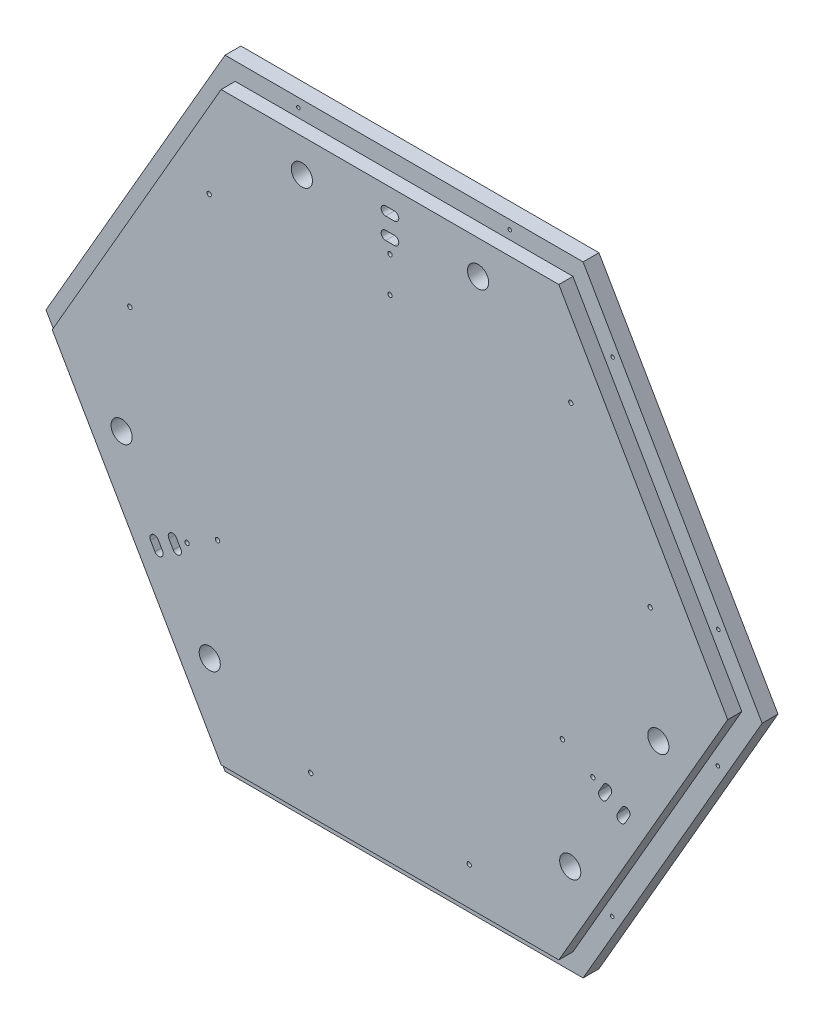
SolidWorks part; units mm, degrees
ref_plane "Front Plane" through (0, 0, 0) normal (0, 0, 1) x (1, 0, 0)
ref_plane "Top Plane" through (0, 0, 0) normal (0, 1, 0) x (1, 0, 0)
ref_plane "Right Plane" through (0, 0, 0) normal (1, 0, 0) x (0, 0, -1)
sketch "Sketch1" plane through (0, 0, 0) normal (0, 0, 1) x (1, 0, 0)
  line L1 (105.6551, 183) -> (-105.6551, 183)
  line L2 (-105.6551, 183) -> (-211.3102, 0)
  line L3 (-211.3102, 0) -> (-105.6551, -183)
  line L4 (-105.6551, -183) -> (105.6551, -183)
  line L5 (105.6551, -183) -> (211.3102, 0)
  line L6 (211.3102, 0) -> (105.6551, 183)
  circle A0 centre (0, 0) radius 183 construction
  circle A1 centre (0, 0) radius 75 construction
  dimension "D1" = 150
  dimension "D2" = 366
extrude "Boss-Extrude1" add sketch "Sketch1" along normal blind 17
sketch "Sketch3" plane through (0, 0, 17) normal (0, 0, 1) x (1, 0, 0)
  line L0 (0, 183) -> (0, 147) construction
  line L1 (211.3102, 0) -> (105.6551, 183) construction
  line L2 (105.6551, 183) -> (-105.6551, 183) construction
  line L3 (-105.6551, 183) -> (-211.3102, 0) construction
  line L4 (-211.3102, 0) -> (-105.6551, -183) construction
  line L5 (-105.6551, -183) -> (105.6551, -183) construction
  line L6 (105.6551, -183) -> (211.3102, 0) construction
  line L7 (158.4826, -91.5) -> (127.3057, -73.5) construction
  line L8 (-158.4826, -91.5) -> (-127.3057, -73.5) construction
  line L9 (-50, 147) -> (0, 147) construction
  line L10 (0, 147) -> (50, 147) construction
  line L11 (-152.3057, -30.1987) -> (-127.3057, -73.5) construction
  line L12 (-127.3057, -73.5) -> (-102.3057, -116.8013) construction
  line L13 (102.3057, -116.8013) -> (127.3057, -73.5) construction
  line L14 (127.3057, -73.5) -> (152.3057, -30.1987) construction
  circle A0 centre (0, 0) radius 183 construction
  circle A1 centre (50, 147) radius 6
  circle A2 centre (-50, 147) radius 6
  circle A3 centre (-152.3057, -30.1987) radius 6
  circle A4 centre (-102.3057, -116.8013) radius 6
  circle A5 centre (102.3057, -116.8013) radius 6
  circle A6 centre (152.3057, -30.1987) radius 6
  dimension "D1" = 366
  dimension "D4" = 12
  dimension "D2" = 36
  dimension "D3" = 50
  dimension "D5" = 147
extrude "Cut-Extrude1" cut sketch "Sketch3" against normal blind 10
sketch "Sketch4" plane through (0, 0, 17) normal (0, 0, 1) x (1, 0, 0)
  line L12 (191.6803, 0) -> (95.8401, 166)
  line L13 (95.8401, 166) -> (-95.8401, 166)
  line L14 (-95.8401, 166) -> (-191.6803, 0)
  line L15 (-191.6803, 0) -> (-95.8401, -166)
  line L16 (-95.8401, -166) -> (95.8401, -166)
  line L17 (95.8401, -166) -> (191.6803, 0)
  line L18 (191.6803, 0) -> (95.8401, 166)
  line L19 (95.8401, 166) -> (-95.8401, 166)
  line L20 (-95.8401, 166) -> (-191.6803, 0)
  line L21 (-191.6803, 0) -> (-95.8401, -166)
  line L22 (-95.8401, -166) -> (95.8401, -166)
  line L23 (95.8401, -166) -> (191.6803, 0)
  dimension "D1" = 17
extrude "Cut-Extrude2" cut sketch "Sketch4" against normal blind 8 flip side to cut
sketch "Sketch5" plane through (0, 0, 17) normal (0, 0, 1) x (1, 0, 0)
  line L0 (50, 147) -> (-50, 147) construction
  line L1 (-152.3057, -30.1987) -> (-102.3057, -116.8013) construction
  line L2 (102.3057, -116.8013) -> (152.3057, -30.1987) construction
  line L3 (97.8609, -56.5) -> (127.3057, -73.5) construction
  line L4 (122.1096, -70.5) -> (132.5019, -76.5) construction
  line L5 (-122.1096, -70.5) -> (-132.5019, -76.5) construction
  line L6 (-97.8609, -56.5) -> (-127.3057, -73.5) construction
  line L7 (-127.3057, -73.5) -> (-115.1814, -66.5) construction
  line L8 (-123.3596, -68.3349) -> (-120.8596, -72.6651) construction
  line L9 (-121.1945, -67.0849) -> (-118.6945, -71.4151)
  line L10 (-125.5246, -69.5849) -> (-123.0246, -73.9151)
  line L11 (-133.7519, -74.3349) -> (-131.2519, -78.6651) construction
  line L12 (-131.5868, -73.0849) -> (-129.0868, -77.4151)
  line L13 (-135.917, -75.5849) -> (-133.417, -79.9151)
  line L14 (127.3057, -73.5) -> (115.1814, -66.5) construction
  line L15 (120.8596, -72.6651) -> (123.3596, -68.3349) construction
  line L16 (118.6945, -71.4151) -> (121.1945, -67.0849)
  line L17 (123.0246, -73.9151) -> (125.5246, -69.5849)
  line L18 (131.2519, -78.6651) -> (133.7519, -74.3349) construction
  line L19 (129.0868, -77.4151) -> (131.5868, -73.0849)
  line L20 (133.417, -79.9151) -> (135.917, -75.5849)
  line L21 (0, 113) -> (0, 147) construction
  line L22 (0, 141) -> (0, 147) construction
  line L23 (0, 147) -> (0, 133) construction
  line L24 (2.5, 141) -> (-2.5, 141) construction
  line L25 (2.5, 138.5) -> (-2.5, 138.5)
  line L26 (2.5, 143.5) -> (-2.5, 143.5)
  line L27 (2.5, 153) -> (-2.5, 153) construction
  line L28 (2.5, 150.5) -> (-2.5, 150.5)
  line L29 (2.5, 155.5) -> (-2.5, 155.5)
  line L30 (105.6551, -183) -> (211.3102, 0) construction
  line L31 (105.6551, 183) -> (-105.6551, 183) construction
  line L32 (0, 147) -> (0, 153) construction
  line L33 (-211.3102, 0) -> (-105.6551, -183) construction
  circle A0 centre (115.1814, -66.5) radius 1.25
  circle A1 centre (97.8609, -56.5) radius 1.25
  arc A2 (118.6945, -71.4151) -> (123.0246, -73.9151) centre (120.8596, -72.6651) ccw
  arc A3 (125.5246, -69.5849) -> (121.1945, -67.0849) centre (123.3596, -68.3349) ccw
  arc A4 (129.0868, -77.4151) -> (133.417, -79.9151) centre (131.2519, -78.6651) ccw
  arc A5 (135.917, -75.5849) -> (131.5868, -73.0849) centre (133.7519, -74.3349) ccw
  circle A6 centre (-115.1814, -66.5) radius 1.25
  circle A7 centre (-97.8609, -56.5) radius 1.25
  arc A8 (-121.1945, -67.0849) -> (-125.5246, -69.5849) centre (-123.3596, -68.3349) ccw
  arc A9 (-123.0246, -73.9151) -> (-118.6945, -71.4151) centre (-120.8596, -72.6651) ccw
  arc A10 (-131.5868, -73.0849) -> (-135.917, -75.5849) centre (-133.7519, -74.3349) ccw
  arc A11 (-133.417, -79.9151) -> (-129.0868, -77.4151) centre (-131.2519, -78.6651) ccw
  circle A12 centre (0, 133) radius 1.25
  circle A13 centre (0, 113) radius 1.25
  arc A14 (2.5, 138.5) -> (2.5, 143.5) centre (2.5, 141) ccw
  arc A15 (-2.5, 143.5) -> (-2.5, 138.5) centre (-2.5, 141) ccw
  arc A16 (2.5, 150.5) -> (2.5, 155.5) centre (2.5, 153) ccw
  arc A17 (-2.5, 155.5) -> (-2.5, 150.5) centre (-2.5, 153) ccw
  point P10 (0, 147)
  point P13 (127.3057, -73.5)
  point P24 (122.1096, -70.5)
  point P34 (-122.1096, -70.5)
  point P40 (-132.5019, -76.5)
  point P50 (132.5019, -76.5)
  point P65 (0, 141)
  point P71 (0, 153)
  dimension "D3" = 2.5
  dimension "D2" = 2.5
  dimension "D5" = 50
  dimension "D8" = 2.5
  dimension "D14" = 2.5
  dimension "D15" = 2.5
  dimension "D18" = 50
  dimension "D19" = 20
  dimension "D13" = 20
  dimension "D7" = 50
  dimension "D9" = 20
  dimension "D4" = 5
  dimension "D6" = 12
  dimension "D10" = 5
  dimension "D11" = 5
  dimension "D12" = 6
  dimension "D16" = 5
  dimension "D17" = 12
  dimension "D22" = 6
  dimension "D26" = 6
  dimension "D27" = 6
  dimension "D28" = 6
  dimension "D29" = 6
extrude "Cut-Extrude3" cut sketch "Sketch5" against normal through all
sketch "Sketch7" plane through (0, 0, 0) normal (0, 0, -1) x (-1, 0, 0)
  line L0 (85.0019, 158.7724) -> (70.2795, 150.2724) construction
  line L1 (85.0019, 158.7724) -> (180.0019, -5.7724) construction
  line L2 (70.2795, 150.2724) -> (165.2795, -14.2724) construction
  line L3 (180.0019, -5.7724) -> (165.2795, -14.2724) construction
  line L4 (-180.0019, -5.7724) -> (-85.0019, 158.7724) construction
  line L5 (-180.0019, -5.7724) -> (-165.2795, -14.2724) construction
  line L6 (-85.0019, 158.7724) -> (-70.2795, 150.2724) construction
  line L7 (-165.2795, -14.2724) -> (-70.2795, 150.2724) construction
  line L8 (95, -153) -> (-95, -153) construction
  line L9 (95, -153) -> (95, -136) construction
  line L10 (-95, -153) -> (-95, -136) construction
  line L11 (95, -136) -> (-95, -136) construction
  line L12 (77.6407, 154.5224) -> (102.6407, 111.2211) construction
  line L13 (211.3102, 0) -> (105.6551, 183) construction
  line L14 (105.6551, 183) -> (-105.6551, 183) construction
  line L15 (-105.6551, 183) -> (-211.3102, 0) construction
  line L16 (-211.3102, 0) -> (-105.6551, -183) construction
  line L17 (-105.6551, -183) -> (105.6551, -183) construction
  line L18 (105.6551, -183) -> (211.3102, 0) construction
  line L19 (102.6407, 111.2211) -> (147.6407, 33.2789) construction
  line L20 (147.6407, 33.2789) -> (172.6407, -10.0224) construction
  line L21 (-45, -144.5) -> (-95, -144.5) construction
  line L22 (95, -144.5) -> (45, -144.5) construction
  line L23 (45, -144.5) -> (-45, -144.5) construction
  line L24 (-102.6407, 111.2211) -> (-77.6407, 154.5224) construction
  line L25 (-172.6407, -10.0224) -> (-147.6407, 33.2789) construction
  line L26 (-147.6407, 33.2789) -> (-102.6407, 111.2211) construction
  line L27 (-158.4826, 91.5) -> (-132.5019, 76.5) construction
  line L28 (0, -153) -> (0, -183) construction
  line L29 (132.5019, 76.5) -> (158.4826, 91.5) construction
  line L30 (0, -144.5) -> (0, -153) construction
  line L31 (125.1407, 72.25) -> (132.5019, 76.5) construction
  line L32 (-132.5019, 76.5) -> (-125.1407, 72.25) construction
  circle A1 centre (147.6407, 33.2789) radius 1.25
  circle A2 centre (102.6407, 111.2211) radius 1.25
  circle A3 centre (45, -144.5) radius 1.25
  circle A4 centre (-45, -144.5) radius 1.25
  circle A5 centre (-147.6407, 33.2789) radius 1.25
  circle A6 centre (-102.6407, 111.2211) radius 1.25
  dimension "D5" = 60.6551
  dimension "D8" = 2.5
  dimension "D1" = 190
  dimension "D2" = 120
  dimension "D3" = 120
  dimension "D4" = 17
  dimension "D6" = 90
  dimension "D7" = 45
  dimension "D9" = 50
  dimension "D10" = 50
  dimension "D11" = 45
  dimension "D13" = 30
  dimension "D14" = 60.6551
extrude "Cut-Extrude5" cut sketch "Sketch7" against normal through all
sketch "Sketch8" plane through (0, 0, 0) normal (0, 0, -1) x (-1, 0, 0)
  line L6 (-101.6136, 176) -> (-203.2273, 0)
  line L7 (-101.6136, 176) -> (-203.2273, 0)
  line L8 (-203.2273, 0) -> (-101.6136, -176)
  line L9 (-203.2273, 0) -> (-101.6136, -176)
  line L10 (-101.6136, -176) -> (101.6136, -176)
  line L11 (-101.6136, -176) -> (101.6136, -176)
  line L12 (101.6136, -176) -> (203.2273, 0)
  line L13 (101.6136, -176) -> (203.2273, 0)
  line L14 (203.2273, 0) -> (101.6136, 176)
  line L15 (203.2273, 0) -> (101.6136, 176)
  line L16 (101.6136, 176) -> (-101.6136, 176)
  line L17 (101.6136, 176) -> (-101.6136, 176)
  line M46 (-105.6551, 183) -> (-211.3102, 0)
  line M47 (-211.3102, 0) -> (-105.6551, -183)
  line M48 (-105.6551, -183) -> (105.6551, -183)
  line M49 (105.6551, -183) -> (211.3102, 0)
  line M50 (211.3102, 0) -> (105.6551, 183)
  line M51 (105.6551, 183) -> (-105.6551, 183)
  dimension "D1" = 7
extrude "Cut-Extrude6" cut sketch "Sketch8" against normal through all contours L17 L15 L13 L11 L9 L7 M51 M46 M47 M48 M49 M50
sketch "Sketch9" plane through (0, 0, 0) normal (0, 0, -1) x (-1, 0, 0)
  line L0 (-152.4205, -88) -> (-148.0903, -85.5) construction
  line L1 (-203.2273, 0) -> (-101.6136, -176) construction
  line L2 (-101.6136, -176) -> (101.6136, -176) construction
  line L3 (101.6136, -176) -> (203.2273, 0) construction
  line L4 (203.2273, 0) -> (101.6136, 176) construction
  line L5 (101.6136, 176) -> (-101.6136, 176) construction
  line L6 (-101.6136, 176) -> (-203.2273, 0) construction
  line L7 (-152.4205, 88) -> (-148.0903, 85.5) construction
  line L8 (-118.0903, -137.4615) -> (-148.0903, -85.5) construction
  line L9 (-148.0903, -85.5) -> (-178.0903, -33.5385) construction
  line L10 (-148.0903, 85.5) -> (-178.3495, 33.6889) construction
  line L11 (-148.0903, 85.5) -> (152.4205, -88) construction
  line L12 (-101.6136, -176) -> (101.6136, 176) construction
  line L13 (-148.0903, 85.5) -> (-118.3502, 137.6107) construction
  line L14 (0, 171) -> (-60, 171) construction
  line L15 (0, 176) -> (0, 171) construction
  line L16 (60, 171) -> (0, 171) construction
  line L17 (118.0903, 137.4615) -> (148.0903, 85.5) construction
  line L18 (152.4205, 88) -> (148.0903, 85.5) construction
  line L19 (148.0903, 85.5) -> (178.0903, 33.5385) construction
  line L20 (148.0903, -85.5) -> (178.3495, -33.6889) construction
  line L21 (152.4205, -88) -> (148.0903, -85.5) construction
  line L22 (148.0903, -85.5) -> (118.3502, -137.6107) construction
  line L23 (0, -171) -> (60, -171) construction
  line L24 (0, -176) -> (0, -171) construction
  line L25 (-60, -171) -> (0, -171) construction
  circle A0 centre (0, 0) radius 176 construction
  circle A1 centre (-178.0903, -33.5385) radius 1
  circle A2 centre (-118.0903, -137.4615) radius 1
  circle A3 centre (-178.3495, 33.6889) radius 1
  circle A4 centre (-118.3502, 137.6107) radius 1
  circle A5 centre (-60, 171) radius 1
  circle A6 centre (60, 171) radius 1
  circle A7 centre (118.0903, 137.4615) radius 1
  circle A8 centre (178.0903, 33.5385) radius 1
  circle A9 centre (178.3495, -33.6889) radius 1
  circle A10 centre (118.3502, -137.6107) radius 1
  circle A11 centre (60, -171) radius 1
  circle A12 centre (-60, -171) radius 1
  dimension "D3" = 2
  dimension "D4" = 2
  dimension "D7" = 2
  dimension "D1" = 5
  dimension "D2" = 5
  dimension "D5" = 60
  dimension "D6" = 60
extrude "Cut-Extrude7" cut sketch "Sketch9" against normal through all contours A4 | A3 | A1 | A2 | A12 | A11 | A10 | A9 | A6 | A5
equation "\"Build Platform Size\" = 150"
equation "\"Rod Diameter\"= 12"
equation "\"Rod Spacing\"= 100"
equation "\"Edge Rod Spacing\"=30"
equation "\"Base Diameter\"= \"Build Platform Size\" + 2 * \"Carriage Depth\" + 2 * \"Rod Diameter\" + 2 * \"Edge Rod Spacing\" + 2 * \"Platform Radius\""
equation "\"Carriage Depth\"= 20"
equation "\"D2@Sketch1\"=\"Base Diameter\""
equation "\"D1@Sketch1\"=\"Build Platform Size\""
equation "\"D1@Sketch3\"=\"Base Diameter\""
equation "\"D2@Sketch3\"=\"Edge Rod Spacing\"+\"Rod Diameter\"/2"
equation "\"D3@Sketch3\"=\"Rod Spacing\"/2"
equation "\"D4@Sketch3\"=\"Rod Diameter\""
equation "\"Platform Radius\"= 46"
